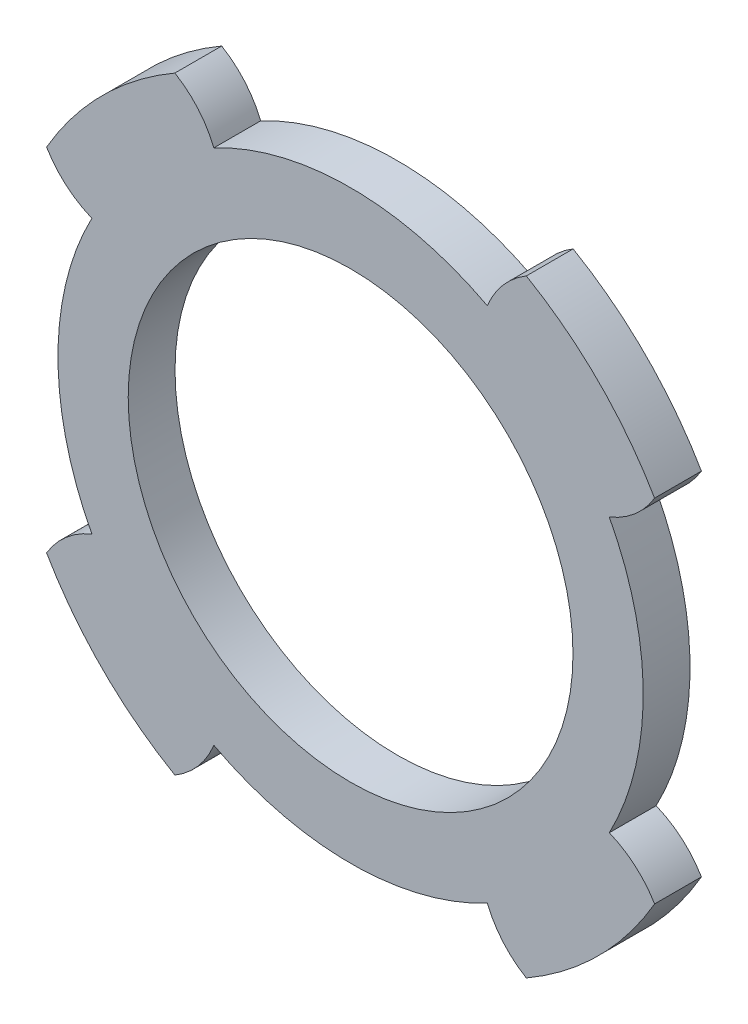
SolidWorks part; units mm, degrees
ref_plane "Front Plane" through (0, 0, 0) normal (0, 0, 1) x (1, 0, 0)
ref_plane "Top Plane" through (0, 0, 0) normal (0, 1, 0) x (1, 0, 0)
ref_plane "Right Plane" through (0, 0, 0) normal (1, 0, 0) x (0, 0, -1)
ref_plane "Output Plane" through (0, 0, 15) normal (0, 0, -1) x (-1, 0, 0)
sketch "CYC Output Sketch" plane through (0, 0, 15) normal (0, 0, 1) x (1, 0, 0)
  line L1 (9.5459, 9.5459) -> (-9.5459, 9.5459) construction
  line L2 (-9.5459, 9.5459) -> (-9.5459, -9.5459) construction
  line L3 (-9.5459, -9.5459) -> (9.5459, -9.5459) construction
  line L4 (9.5459, -9.5459) -> (9.5459, 9.5459) construction
  circle A0 centre (0, 0) radius 13.5 construction
sketch "Sketch3" plane through (0, 0, 15) normal (0, 0, -1) x (-1, 0, 0)
  circle A0 centre (-9.5459, 9.5459) radius 4
  circle A1 centre (9.5459, 9.5459) radius 4
  circle A2 centre (9.5459, -9.5459) radius 4
  circle A3 centre (-9.5459, -9.5459) radius 4
  dimension "D1" = 8
extrude "Boss-Extrude1" add sketch "Sketch3" along normal blind 11
sketch "Sketch6" plane through (0, 0, 15) normal (0, 0, 1) x (1, 0, 0)
  arc A0 (-7.5062, 12.9868) -> (-12.9868, 7.5062) centre (0, 0) ccw
  arc A5 (-11.0518, 5.8402) -> (-11.0518, -5.8402) centre (0, 0) ccw
  circle A6 centre (0, 0) radius 9.5
  arc A7 (-5.8402, 11.0518) -> (-7.5062, 12.9868) centre (-9.5459, 9.5459) ccw
  arc A8 (11.0518, 5.8402) -> (12.9868, 7.5062) centre (9.5459, 9.5459) ccw
  arc A9 (5.8402, -11.0518) -> (7.5062, -12.9868) centre (9.5459, -9.5459) ccw
  arc A10 (-11.0518, -5.8402) -> (-12.9868, -7.5062) centre (-9.5459, -9.5459) ccw
  arc A11 (5.8402, 11.0518) -> (-5.8402, 11.0518) centre (0, 0) ccw
  arc A12 (11.0518, -5.8402) -> (11.0518, 5.8402) centre (0, 0) ccw
  arc A13 (-5.8402, -11.0518) -> (5.8402, -11.0518) centre (0, 0) ccw
  arc A14 (7.5062, 12.9868) -> (5.8402, 11.0518) centre (9.5459, 9.5459) ccw
  arc A15 (12.9868, -7.5062) -> (11.0518, -5.8402) centre (9.5459, -9.5459) ccw
  arc A16 (-7.5062, -12.9868) -> (-5.8402, -11.0518) centre (-9.5459, -9.5459) ccw
  arc A17 (-12.9868, 7.5062) -> (-11.0518, 5.8402) centre (-9.5459, 9.5459) ccw
  arc A18 (12.9868, 7.5062) -> (7.5062, 12.9868) centre (0, 0) ccw
  arc A19 (7.5062, -12.9868) -> (12.9868, -7.5062) centre (0, 0) ccw
  arc A20 (-12.9868, -7.5062) -> (-7.5062, -12.9868) centre (0, 0) ccw
  dimension "D2" = 30
  dimension "D3" = 25
  dimension "D4" = 8
  dimension "D1" = 19
  dimension "D5" = 27
extrude "Boss-Extrude6" add sketch "Sketch6" along normal blind 2 contours A6 | A0 A17 A5 A10 A20 A16 A13 A9 A19 A15 A12 A8 A18 A14 A11 A7
sketch "Sketch7" plane through (0, 0, 4) normal (0, 0, -1) x (-1, 0, 0)
  circle A0 centre (0, 0) radius 19.1912
extrude "Cut-Extrude1" cut sketch "Sketch7" against normal up to surface (11 mm away) up to face at (9.8762, 0, 15)
equation "\"RingPinShaft\"= 5"
equation "\"CenterBearingOut\"=32"
equation "\"RingPostIn\"=5"
equation "\"CamBearingOut\"=15.15"
equation "\"DiskOutputShaft\"=10"
equation "\"CenterShaft\"=25"
equation "\"Eccentricity\"=2"
equation "\"CycCamShaft\"=10"
equation "\"D2@Sketch6\"=\"OutputBearing\""
equation "\"OutputBearing\"=30"
